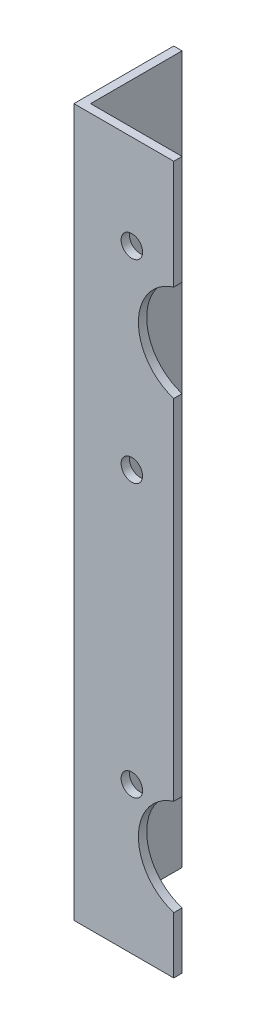
SolidWorks part; units mm, degrees
material "1060 Alloy"
ref_plane "Front Plane" through (0, 0, 0) normal (0, 0, 1) x (1, 0, 0)
ref_plane "Top Plane" through (0, 0, 0) normal (0, 1, 0) x (1, 0, 0)
ref_plane "Right Plane" through (0, 0, 0) normal (1, 0, 0) x (0, 0, -1)
sketch "Sketch1" plane through (0, 0, 0) normal (0, 1, 0) x (1, 0, 0)
  line L0 (0, 0) -> (19.05, 0)
  line L1 (19.05, 0) -> (19.05, 1.5875)
  line L2 (19.05, 1.5875) -> (1.5875, 1.5875)
  line L3 (1.5875, 1.5875) -> (1.5875, 19.05)
  line L4 (1.5875, 19.05) -> (0, 19.05)
  line L5 (0, 19.05) -> (0, 0)
  dimension "D1" = 19.05
  dimension "D2" = 19.05
  dimension "D3" = 1.5875
  dimension "D4" = 1.5875
extrude "Boss-Extrude1" add sketch "Sketch1" along normal blind 135
sketch "Sketch2" plane through (1.5875, 0, 0) normal (1, 0, 0) x (0, 0, -1)
  line L0 (19.05, 135) -> (19.05, 0) construction
  line L1 (1.5875, 135) -> (19.05, 135) construction
  line L2 (19.05, 135) -> (0, 135) construction
  circle A0 centre (11.05, 117) radius 2.05
  circle A1 centre (11.05, 80) radius 2.05
  circle A2 centre (11.05, 28) radius 2.05
  point P12 (10.3187, 135)
  dimension "D1" = 4.1
  dimension "D2" = 8
  dimension "D3" = 18
  dimension "D4" = 55
  dimension "D5" = 107
extrude "Cut-Extrude1" cut sketch "Sketch2" against normal through all
sketch "Sketch3" plane through (0, 0, -1.5875) normal (0, 0, -1) x (-1, 0, 0)
  line L0 (-19.05, 135) -> (-19.05, 0) construction
  line L2 (-19.05, 135) -> (-1.5875, 135) construction
  circle A0 centre (-11.05, 117) radius 2.05
  circle A1 centre (-11.05, 80) radius 2.05
  circle A2 centre (-11.05, 28) radius 2.05
  dimension "D1" = 8
  dimension "D2" = 4.1
  dimension "D5" = 107
  dimension "D3" = 18
  dimension "D4" = 55
extrude "Cut-Extrude2" cut sketch "Sketch3" against normal through all
sketch "Sketch4" plane through (0, 0, -1.5875) normal (0, 0, -1) x (-1, 0, 0)
  circle A0 centre (-21.95, 105) radius 9.65
  circle A1 centre (-21.95, 20) radius 9.65
extrude "Cut-Extrude3" cut sketch "Sketch4" against normal blind 10
